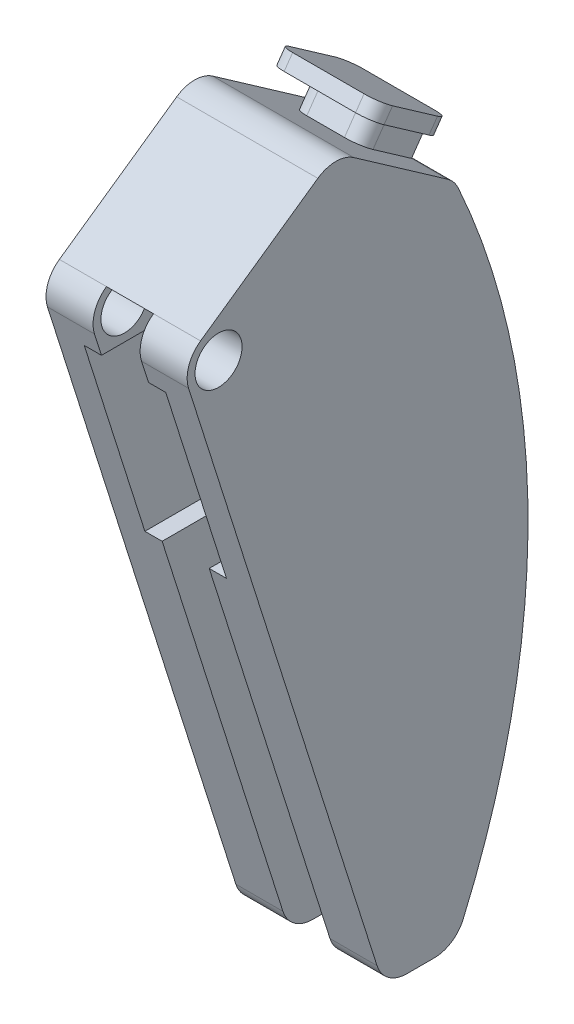
SolidWorks part; units mm, degrees
material "Custom Plastic"
ref_plane "Front Plane" through (0, 0, 0) normal (0, 0, 1) x (1, 0, 0)
ref_plane "Top Plane" through (0, 0, 0) normal (0, 1, 0) x (1, 0, 0)
ref_plane "Right Plane" through (0, 0, 0) normal (1, 0, 0) x (0, 0, -1)
sketch "Sketch1" plane through (0, 0, 0) normal (1, 0, 0) x (0, 0, -1)
  line L0 (0, 0) -> (57.5505, 26.8363) construction
  line L1 (0, 0) -> (52.0162, 36.4221) construction
  line L2 (0, 0) -> (63.5, 0) construction
  line L3 (57.5505, -26.8363) -> (0, 0) construction
  line L4 (56.9869, 27.2309) -> (49.3952, 32.5467)
  line L5 (46.4815, 32.5467) -> (36.9827, 25.8955)
  line L6 (55.909, -26.8363) -> (53.6948, -26.8363)
  line L7 (36.0183, 23.0472) -> (51.2736, -25.064)
  circle A0 centre (0, 0) radius 63.5 construction
  arc A1 (58.2385, -25.3086) -> (57.8438, 26.1982) centre (0, 0) ccw
  arc A2 (53.6948, -26.8363) -> (51.2736, -25.064) centre (53.6948, -24.2963) cw
  arc A3 (55.909, -26.8363) -> (58.2385, -25.3086) centre (55.909, -24.2963) ccw
  arc A4 (49.3952, 32.5467) -> (46.4815, 32.5467) centre (47.9383, 30.466) ccw
  arc A5 (36.0183, 23.0472) -> (36.9827, 25.8955) centre (38.4395, 23.8149) cw
  arc A6 (57.8438, 26.1982) -> (56.9869, 27.2309) centre (55.53, 25.1503) ccw
  point P12 (51.8355, -26.8363)
  point P18 (47.9383, 33.5668)
  point P21 (35.4545, 24.8255)
  dimension "D1" = 127
  dimension "D8" = 2.54
  dimension "D9" = 2.54
  dimension "D2" = 25
  dimension "D3" = 35
  dimension "D4" = 25
  dimension "D5" = 110
  dimension "D6" = 15.24
  dimension "D7" = 5.715
extrude "Boss-Extrude1" add sketch "Sketch1" along normal mid plane 11.43
sketch "Sketch4" plane through (0, 0, 0) normal (0, 0, 1) x (1, 0, 0)
  line L1 (1.905, -29.3763) -> (-1.905, -29.3763)
  line L2 (1.905, -29.3763) -> (1.905, 25.8955)
  line L3 (1.905, 25.8955) -> (-1.905, 25.8955)
  line L4 (-1.905, -29.3763) -> (-1.905, 25.8955)
  line L5 (1.905, -29.3763) -> (-1.905, 25.8955) construction
  line L6 (1.905, 25.8955) -> (-1.905, -29.3763) construction
  line L7 (5.715, -26.8363) -> (-5.715, -26.8363) construction
  line L8 (5.715, 25.8955) -> (-5.715, 25.8955) construction
  point P0 (0, -1.7404)
  dimension "D1" = 3.81
  dimension "D2" = 2.54
extrude "Cut-Extrude3" cut sketch "Sketch4" against normal through all
sketch "Sketch6" plane through (5.715, 0, 0) normal (1, 0, 0) x (0, 0, -1)
  circle A0 centre (38.4395, 23.8149) radius 2.54 construction
  arc A3 (36.9827, 25.8955) -> (36.0183, 23.0472) centre (38.4395, 23.8149) ccw construction
  circle A4 centre (38.4395, 23.8149) radius 1.905
  dimension "D1" = 3.81
  dimension "D2" = 5.08
  dimension "D3" = 5.08
extrude "Cut-Extrude5" cut sketch "Sketch6" against normal through all
sketch "Sketch5" plane through (0, 0, 0) normal (0, 0, 1) x (1, 0, 0)
  line L1 (-3.302, 21.2749) -> (3.302, 21.2749)
  line L2 (-3.302, 21.2749) -> (-3.302, 5.7809)
  line L3 (-3.302, 5.7809) -> (3.302, 5.7809)
  line L4 (3.302, 21.2749) -> (3.302, 5.7809)
  line L5 (-3.302, 21.2749) -> (3.302, 5.7809) construction
  line L6 (-3.302, 5.7809) -> (3.302, 21.2749) construction
  line L10 (-1.905, 23.8149) -> (-5.715, 23.8149) construction
  point P0 (0, 13.5279)
  dimension "D1" = 6.604
  dimension "D2" = 15.494
  dimension "D3" = 2.54
extrude "Cut-Extrude4" cut sketch "Sketch5" against normal blind 52.07
sketch "Sketch7" plane through (0, 45.0473, -31.5425) normal (0, 0.8192, -0.5736) x (1, 0, 0)
  line L0 (5.715, 31.062) -> (-5.715, 31.062) construction
  line L1 (1.524, 25.982) -> (-1.524, 25.982)
  line L2 (2.794, 27.252) -> (2.794, 31.062)
  line L3 (2.794, 31.062) -> (-2.794, 31.062)
  line L4 (-2.794, 27.252) -> (-2.794, 31.062)
  line L5 (2.794, 25.982) -> (-2.794, 31.062) construction
  line L6 (2.794, 31.062) -> (-2.794, 25.982) construction
  arc A0 (-2.794, 27.252) -> (-1.524, 25.982) centre (-1.524, 27.252) ccw
  arc A1 (2.794, 27.252) -> (1.524, 25.982) centre (1.524, 27.252) cw
  point P0 (0, 28.522)
  dimension "D3" = 1.27
  dimension "D1" = 5.588
  dimension "D2" = 5.08
extrude "Boss-Extrude2" add sketch "Sketch7" along normal blind 1.905
sketch "Sketch9" plane through (0, 46.6078, -32.6351) normal (0, 0.8192, -0.5736) x (1, 0, 0)
  line L0 (2.794, 31.062) -> (-2.794, 31.062) construction
  line L1 (2.8908, 31.062) -> (-2.8908, 31.062)
  line L2 (4.1608, 29.792) -> (4.1608, 25.347)
  line L3 (2.8908, 24.077) -> (-2.8908, 24.077)
  line L4 (-4.1608, 29.792) -> (-4.1608, 25.347)
  line L5 (4.1608, 31.062) -> (-4.1608, 24.077) construction
  line L6 (4.1608, 24.077) -> (-4.1608, 31.062) construction
  line L7 (2.794, 27.252) -> (2.794, 31.062) construction
  line L8 (-1.524, 25.982) -> (1.524, 25.982) construction
  arc A0 (-4.1608, 29.792) -> (-2.8908, 31.062) centre (-2.8908, 29.792) cw
  arc A1 (2.8908, 31.062) -> (4.1608, 29.792) centre (2.8908, 29.792) cw
  arc A2 (-4.1608, 25.347) -> (-2.8908, 24.077) centre (-2.8908, 25.347) ccw
  arc A3 (4.1608, 25.347) -> (2.8908, 24.077) centre (2.8908, 25.347) cw
  point P0 (0, 27.5695)
  dimension "D3" = 1.27
  dimension "D1" = 1.3668
  dimension "D2" = 1.905
extrude "Boss-Extrude3" add sketch "Sketch9" along normal blind 1.2
